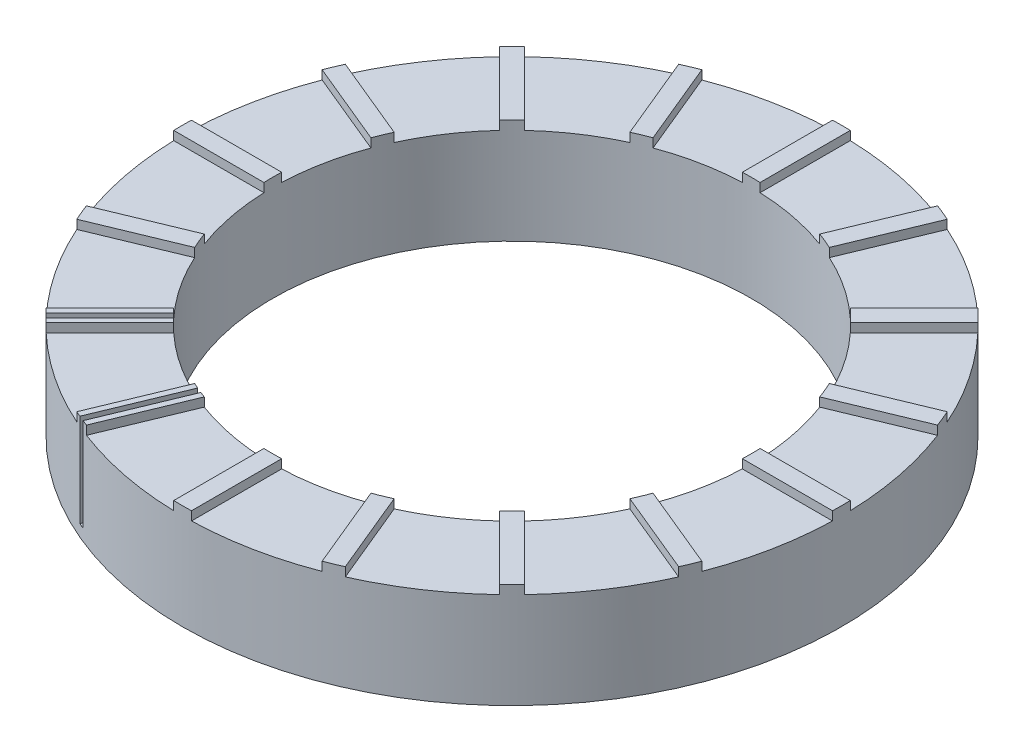
SolidWorks part; units mm, degrees
ref_plane "Front Plane" through (0, 0, 0) normal (0, 0, 1) x (1, 0, 0)
ref_plane "Top Plane" through (0, 0, 0) normal (0, 1, 0) x (1, 0, 0)
ref_plane "Right Plane" through (0, 0, 0) normal (1, 0, 0) x (0, 0, -1)
sketch "Sketch1" plane through (0, 0, 0) normal (0, 1, 0) x (1, 0, 0)
  circle A0 centre (0, 0) radius 16.2
  circle A1 centre (0, 0) radius 22.3
  dimension "D1" = 44.6
  dimension "D2" = 32.4
extrude "Boss-Extrude1" add sketch "Sketch1" along normal blind 6.5
sketch "Sketch2" plane through (0, 6.5, 0) normal (0, 1, 0) x (1, 0, 0)
  line L0 (-0.6, 22.2919) -> (-0.6, 16.1889)
  line L1 (0.6, 22.2919) -> (0.6, 16.1889)
  line L2 (0, 23.1086) -> (0, 0) construction
  circle A0 centre (0, 0) radius 22.3 construction
  circle A1 centre (0, 0) radius 16.2 construction
  circle A2 centre (0, 0) radius 16.2
  circle A3 centre (0, 0) radius 22.3
  circle M4 centre (0, 0) radius 22.3
  circle M5 centre (0, 0) radius 16.2
  dimension "D1" = 1.2
extrude "Boss-Extrude2" add sketch "Sketch2" along normal blind 0.6 contours L2 A2 L1 M4 | L2 A3 L0 M5
pattern_circular "CirPattern1" count 16 over 360 about axis through (0, 0, 0) along (0, 1, 0) of "Boss-Extrude2"
sketch "Sketch3" plane through (0, 7.1, 0) normal (0, 1, 0) x (1, 0, 0)
  line L0 (-15.7685, -15.7685) -> (-11.4551, -11.4551) construction
  line L1 (-6.1995, -14.9668) -> (-8.5338, -20.6025) construction
  line L2 (-15.9093, -15.6264) -> (-11.5957, -11.3128)
  line L3 (-11.3128, -11.5957) -> (-15.6264, -15.9093)
  line L4 (-6.0142, -15.0422) -> (-8.3487, -20.6782)
  line L5 (-6.3838, -14.8892) -> (-8.7183, -20.5251)
  arc A0 (-16.187, -15.3385) -> (-15.3385, -16.187) centre (0, 0) ccw construction
  arc A1 (-11.8715, -11.023) -> (-11.023, -11.8715) centre (0, 0) ccw construction
  arc A2 (-6.7495, -14.727) -> (-5.6409, -15.1862) centre (0, 0) ccw construction
  arc A3 (-9.0851, -20.3654) -> (-7.9764, -20.8247) centre (0, 0) ccw construction
  arc A4 (-8.7183, -20.5251) -> (-8.3487, -20.6782) centre (0, 0) ccw
  arc A5 (-6.3838, -14.8892) -> (-6.0142, -15.0422) centre (0, 0) ccw
  arc A6 (-11.5957, -11.3128) -> (-11.3128, -11.5957) centre (0, 0) ccw
  arc A7 (-15.9093, -15.6264) -> (-15.6264, -15.9093) centre (0, 0) ccw
  dimension "D1" = 0.4
  dimension "D2" = 0.4
extrude "Cut-Extrude1" cut sketch "Sketch3" against normal offset from surface (6.3 mm away) 0.8 up to face at (0, 0, 22.3)
